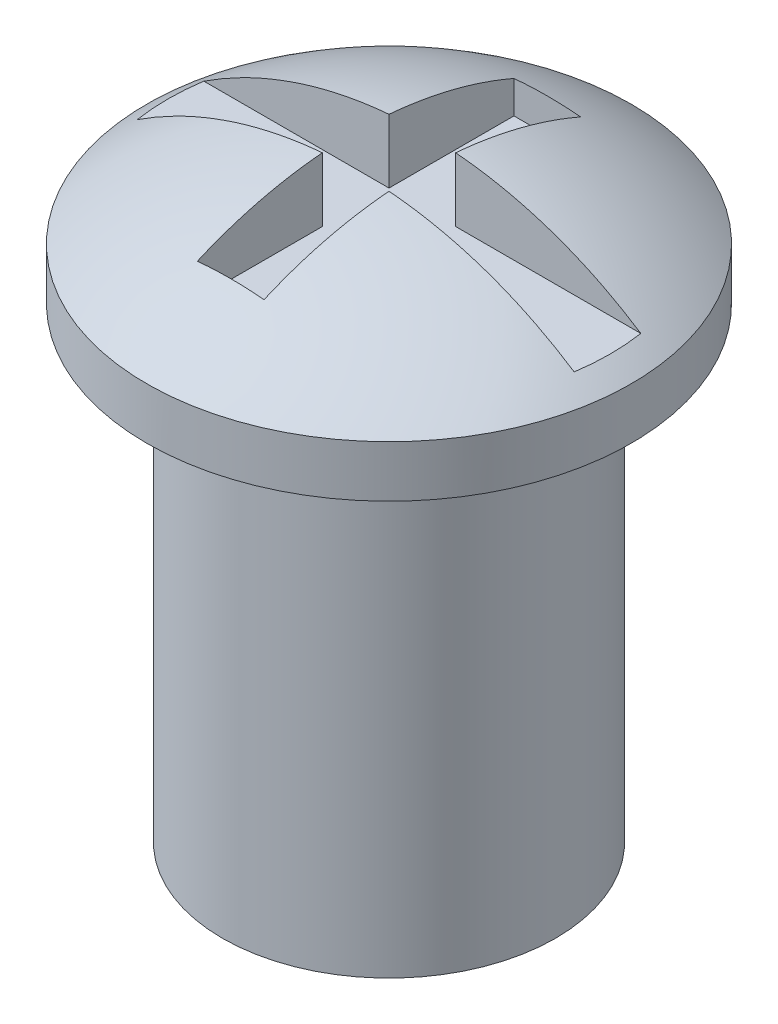
SolidWorks part; units mm, degrees
ref_plane "前视基准面" through (0, 0, 0) normal (0, 0, 1) x (1, 0, 0)
ref_plane "上视基准面" through (0, 0, 0) normal (0, 1, 0) x (1, 0, 0)
ref_plane "右视基准面" through (0, 0, 0) normal (1, 0, 0) x (0, 0, -1)
sketch "草图1" plane through (0, 0, 0) normal (0, 1, 0) x (1, 0, 0)
  circle A0 centre (0, 0) radius 2.5
  dimension "D1" = 5
extrude "拉伸1" add sketch "草图1" along normal blind 7
sketch "草图2" plane through (0, 7, 0) normal (0, 1, 0) x (-1, 0, 0)
  circle A0 centre (0, 0) radius 3.635
  dimension "D1" = 7.27
extrude "拉伸2" add sketch "草图2" along normal blind 2
sketch "草图3" plane through (0, 9, 0) normal (0, 1, 0) x (-1, 0, 0)
  line L0 (4.0624, 0) -> (-4.2778, 0) construction
  line L1 (0, -3.5166) -> (0, 3.738) construction
  line L3 (5.386, -0.5) -> (-5.386, -0.5)
  line L4 (5.386, -0.5) -> (5.386, 0.5)
  line L5 (5.386, 0.5) -> (-5.386, 0.5)
  line L6 (-5.386, -0.5) -> (-5.386, 0.5)
  dimension "D1" = 1
extrude "切除-拉伸1" cut sketch "草图3" against normal blind 1
sketch "草图4" plane through (0, 9, 0) normal (0, 1, 0) x (-1, 0, 0)
  line L0 (0, -3.8639) -> (0, 3.6765) construction
  line L1 (1.7727, 0) -> (-1.7019, 0) construction
  line L2 (0.5, -2.375) -> (-0.5, -2.375)
  line L3 (0.5, -2.375) -> (0.5, 2.375)
  line L4 (0.5, 2.375) -> (-0.5, 2.375)
  line L5 (-0.5, -2.375) -> (-0.5, 2.375)
  dimension "D1" = 1
  dimension "D2" = 4.75
extrude "切除-拉伸2" cut sketch "草图4" against normal blind 1
sketch "草图5" plane through (0, 0, 0) normal (1, 0, 0) x (0, 0, -1)
  line L0 (0, -2.1059) -> (0, 12.2815) construction
  line L1 (-0.5, 9) -> (-3.635, 9) construction
  line L2 (0, 10.9998) -> (-4.5494, 10.9998)
  line L3 (-4.5494, 6.9119) -> (-4.5494, 10.9998)
  line L5 (0, 10.9998) -> (0, 9)
  arc A2 (0, 9) -> (-4.5494, 6.9119) centre (0, 3) ccw
  dimension "D1" = 6
revolve "切除-旋转16" cut sketch "草图5" angle 360 about L0
